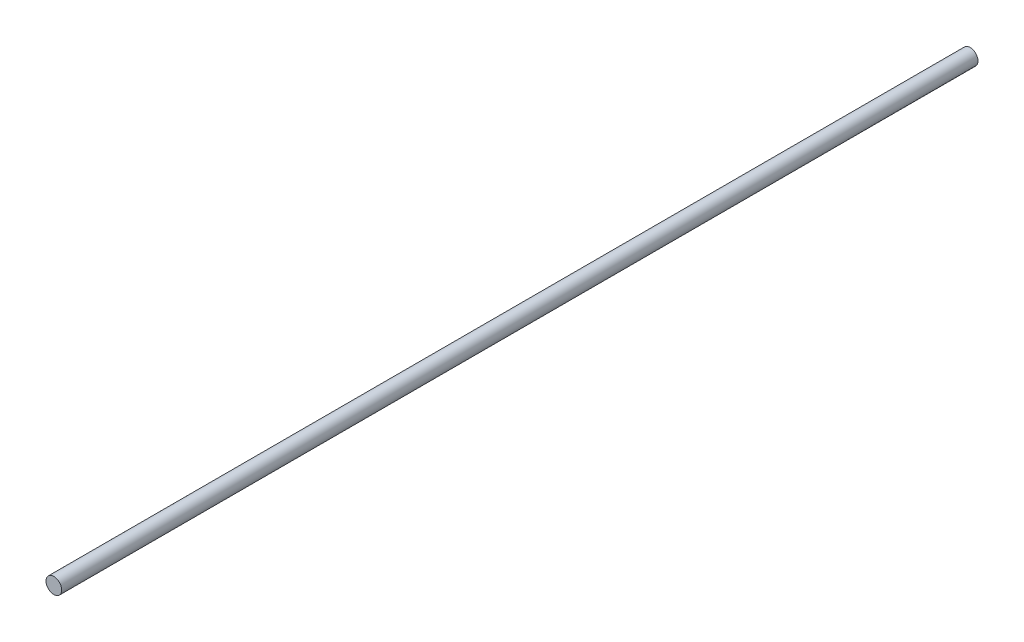
SolidWorks part; units mm, degrees
ref_plane "Front Plane" through (0, 0, 0) normal (0, 0, 1) x (1, 0, 0)
ref_plane "Top Plane" through (0, 0, 0) normal (0, 1, 0) x (1, 0, 0)
ref_plane "Right Plane" through (0, 0, 0) normal (1, 0, 0) x (0, 0, -1)
sketch "Sketch1" plane through (0, 0, 0) normal (0, 0, 1) x (1, 0, 0)
  circle A0 centre (-32.4095, 8.4317) radius 3
extrude "Boss-Extrude1" add sketch "Sketch1" along normal blind 350
